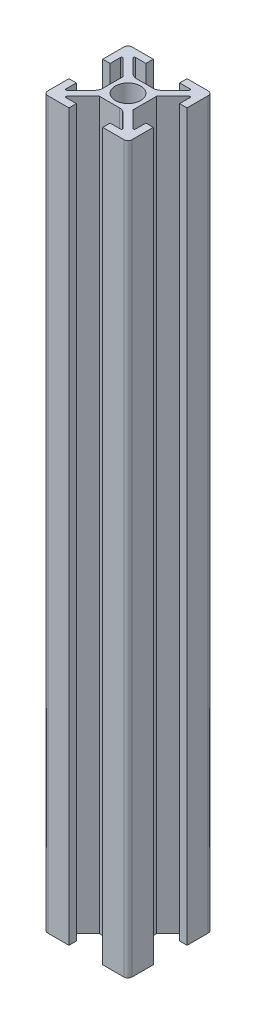
SolidWorks part; units mm, degrees
material "6063-T5"
ref_plane "Plano frontal" through (0, 0, 0) normal (0, 0, 1) x (1, 0, 0)
ref_plane "Plano superior" through (0, 0, 0) normal (0, 1, 0) x (1, 0, 0)
ref_plane "Plano direito" through (0, 0, 0) normal (1, 0, 0) x (0, 0, -1)
sketch "Esboço1" plane through (0, 0, 0) normal (0, 1, 0) x (1, 0, 0)
  line L1 (-10, 10) -> (10, 10)
  line L2 (-10, 10) -> (-10, -10)
  line L3 (-10, -10) -> (10, -10)
  line L4 (10, 10) -> (10, -10)
  line L5 (-10, 10) -> (10, -10) construction
  line L6 (-10, -10) -> (10, 10) construction
  circle A0 centre (0, 0) radius 3
  dimension "D1" = 6
  dimension "D2" = 20
  dimension "D3" = 20
extrude "Ressalto-extrusão1" add sketch "Esboço1" along normal mid plane 172
sketch "Esboço2" plane through (0, 86, 0) normal (0, 1, 0) x (1, 0, 0)
  line L0 (10, 10) -> (-10, 10) construction
  line L1 (-4, 4) -> (4, 4)
  line L2 (-4, 4) -> (-4, -4)
  line L3 (-4, -4) -> (4, -4)
  line L4 (4, 4) -> (4, -4)
  line L5 (-4, 4) -> (4, -4) construction
  line L6 (-4, -4) -> (4, 4) construction
  line L7 (0, 10) -> (0, -10) construction
  line L8 (-10, -10) -> (10, -10) construction
  line L9 (-4, 10) -> (4, 10)
  line L10 (-4, 10) -> (-4, 8.25)
  line L11 (4, 10) -> (4, 8.25)
  line L12 (-4, 8.25) -> (4, 8.25)
  line L13 (-7.05, 8.25) -> (7.05, 8.25)
  line L14 (-7.05, 8.25) -> (-2.8, 4)
  line L15 (7.05, 8.25) -> (2.8, 4)
  line L16 (2.8, 4) -> (-2.8, 4)
  point P0 (0, 0)
  point P19 (0, 8.25)
  line M7 (10, 10) -> (-10, 10)
  dimension "D1" = 8
  dimension "D2" = 8
  dimension "D3" = 1.75
  dimension "D4" = 8
  dimension "D5" = 14.1
  dimension "D6" = 45
  dimension "D7" = 45
extrude "Corte-extrusão1" cut sketch "Esboço2" against normal through all contours L15 L13 L12 L14 L1 | L10 L12 L11 M7
pattern_circular "PadrãoCircular2" count 4 over 360 about axis through (0, 0, 0) along (0, 1, 0) of "Corte-extrusão1"
fillet "Filete2" radius 1 4 edges at (10, 0, 10) (-10, 0, 10) (-10, 0, -10) (10, 0, -10)
fillet "Filete3" radius 2 4 edges at (2.8, 0, 4) (-4, 0, 2.8) (2.8, 0, -4) (-2.8, 0, -4)
fillet "Filete4" radius 0.25 8 edges at (8.25, 0, 7.05) (7.05, 0, 8.25) (-8.25, 0, 7.05) (-7.05, 0, 8.25) (8.25, 0, -7.05) (7.05, 0, -8.25) (-8.25, 0, -7.05) (-7.05, 0, -8.25)
